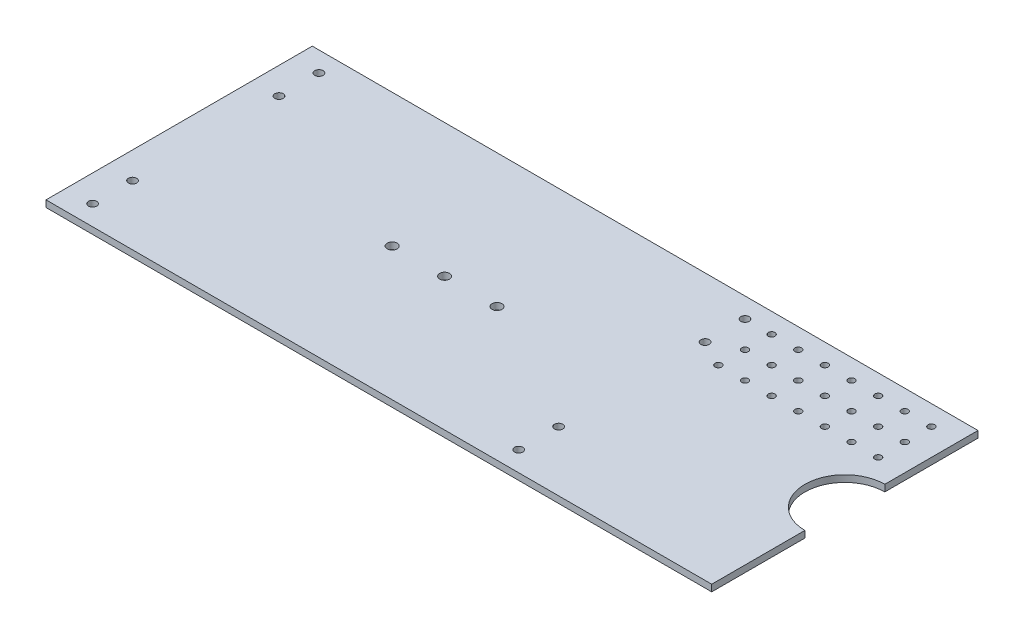
SolidWorks part; units mm, degrees
ref_plane "Front Plane" through (0, 0, 0) normal (0, 0, 1) x (1, 0, 0)
ref_plane "Top Plane" through (0, 0, 0) normal (0, 1, 0) x (1, 0, 0)
ref_plane "Right Plane" through (0, 0, 0) normal (1, 0, 0) x (0, 0, -1)
sketch "Sketch1" plane through (0, 0, 0) normal (0, 1, 0) x (1, 0, 0)
  line L1 (-317.5, -127) -> (317.5, -127)
  line L2 (-317.5, -127) -> (-317.5, 127)
  line L3 (-317.5, 127) -> (317.5, 127)
  line L4 (317.5, -127) -> (317.5, 127)
  line L5 (-317.5, -127) -> (317.5, 127) construction
  line L6 (-317.5, 127) -> (317.5, -127) construction
  point P0 (0, 0)
  dimension "D1" = 254
  dimension "D2" = 635
extrude "Boss-Extrude1" add sketch "Sketch1" along normal blind 6.35
sketch "Sketch2" plane through (0, 0, 0) normal (0, 1, 0) x (-1, 0, 0)
  line L1 (-317.5, 0) -> (317.5, 0) construction
  line L3 (3.4925, 0) -> (-3.4925, 0) construction
  line L4 (-317.5, 127) -> (-317.5, -127) construction
  line L5 (317.5, -127) -> (317.5, 127) construction
  circle A0 centre (114.3, 0) radius 4.7625
  circle A1 centre (64.3, 0) radius 4.7625
  circle A2 centre (14.3, 0) radius 4.7625
  dimension "D1" = 9.525
  dimension "D3" = 50
  dimension "D2" = 203.2
  dimension "D4" = 50
extrude "Cut-Extrude2" cut sketch "Sketch2" against normal through all and the other way through all
sketch "Sketch3" plane through (0, 0, 0) normal (0, 1, 0) x (1, 0, 0)
  line L0 (317.5, 127) -> (-317.5, 127) construction
  line L1 (-317.5, 127) -> (-317.5, -127) construction
  line L2 (-317.5, -127) -> (317.5, -127) construction
  circle A0 centre (-292.1, 107.95) radius 3.9688
  circle A1 centre (-292.1, 69.85) radius 3.9688
  circle A2 centre (-292.1, -69.85) radius 3.9688
  circle A3 centre (-292.1, -107.95) radius 3.9688
  circle A4 centre (114.3, 107.95) radius 3.9687
  circle A5 centre (114.3, 69.85) radius 3.9687
  circle A6 centre (114.3, -69.85) radius 3.9687
  circle A7 centre (114.3, -107.95) radius 3.9687
  dimension "D6" = 7.9375
  dimension "D1" = 19.05
  dimension "D2" = 38.1
  dimension "D3" = 25.4
  dimension "D4" = 38.1
  dimension "D5" = 19.05
  dimension "D7" = 406.4
extrude "Cut-Extrude4" cut sketch "Sketch3" along normal through all
sketch "Sketch4" plane through (0, 0, 0) normal (0, 1, 0) x (1, 0, 0)
  line L0 (317.5, -127) -> (317.5, 127) construction
  circle A0 centre (317.5, 0) radius 38.1
  dimension "D1" = 76.2
extrude "Cut-Extrude6" cut sketch "Sketch4" along normal through all
sketch "Sketch5" plane through (0, 6.35, 0) normal (0, 1, 0) x (1, 0, 0)
  line L0 (317.5, 127) -> (-317.5, 127) construction
  circle A0 centre (139.7, 107.95) radius 3.175
  circle A1 centre (114.3, 107.95) radius 3.9687 construction
  circle A2 centre (165.1, 107.95) radius 3.175
  circle A3 centre (190.5, 107.95) radius 3.175
  circle A5 centre (215.9, 107.95) radius 3.175
  circle A6 centre (241.3, 107.95) radius 3.175
  circle A7 centre (266.7, 107.95) radius 3.175
  circle A8 centre (292.1, 107.95) radius 3.175
  circle A11 centre (165.1, 82.55) radius 3.175
  circle A12 centre (190.5, 82.55) radius 3.175
  circle A13 centre (215.9, 82.55) radius 3.175
  circle A14 centre (241.3, 82.55) radius 3.175
  circle A15 centre (266.7, 82.55) radius 3.175
  circle A16 centre (292.1, 82.55) radius 3.175
  circle A19 centre (165.1, 57.15) radius 3.175
  circle A20 centre (190.5, 57.15) radius 3.175
  circle A21 centre (215.9, 57.15) radius 3.175
  circle A22 centre (241.3, 57.15) radius 3.175
  circle A23 centre (266.7, 57.15) radius 3.175
  circle A24 centre (292.1, 57.15) radius 3.175
  circle A27 centre (139.7, 82.55) radius 3.175
  circle A28 centre (139.7, 57.15) radius 3.175
  dimension "D1" = 6.35
  dimension "D2" = 25.4
  dimension "D6" = 25.4
  dimension "D7" = 25.4
  dimension "D3" = 7
  dimension "D4" = 19.05
  dimension "D5" = 3
extrude "Cut-Extrude7" cut sketch "Sketch5" against normal through all
